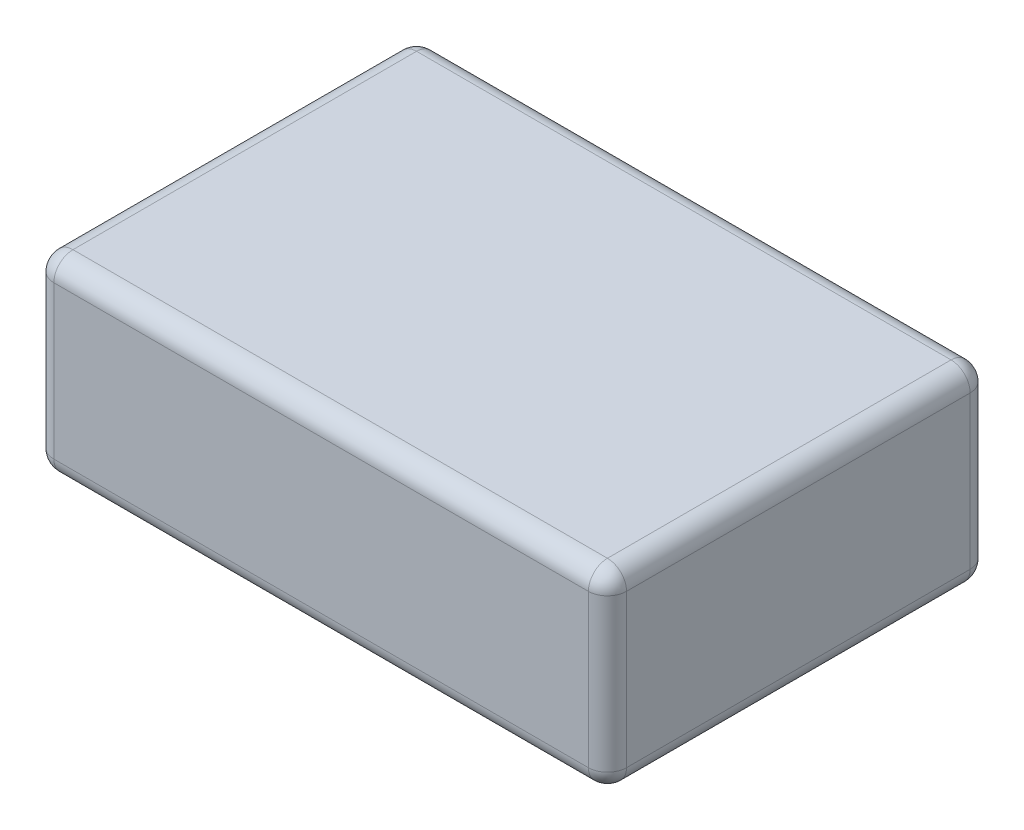
SolidWorks part; units mm, degrees
material "NdFeB"
ref_plane "Front Plane" through (0, 0, 0) normal (0, 0, 1) x (1, 0, 0)
ref_plane "Top Plane" through (0, 0, 0) normal (0, 1, 0) x (1, 0, 0)
ref_plane "Right Plane" through (0, 0, 0) normal (1, 0, 0) x (0, 0, -1)
sketch "Sketch1" plane through (0, 0, 0) normal (1, 0, 0) x (0, 0, -1)
  line L5 (-10, 5) -> (10, 5)
  line L6 (-10, 5) -> (-10, -5)
  line L7 (-10, -5) -> (10, -5)
  line L8 (10, 5) -> (10, -5)
  line L9 (-10, 5) -> (10, -5) construction
  line L10 (-10, -5) -> (10, 5) construction
  point P0 (0, 0)
  dimension "D1" = 20
  dimension "D2" = 10
extrude "Boss-Extrude1" add sketch "Sketch1" along normal mid plane 30
fillet "Fillet1" radius 1 12 edges at (15, 0, 10) (15, -5, 0) (15, 0, -10) (0, -5, -10) (0, 5, -10) (-15, 0, -10) (0, -5, 10) (-15, 0, 10) (-15, -5, 0) (-15, 5, 0) (15, 5, 0) (0, 5, 10)
